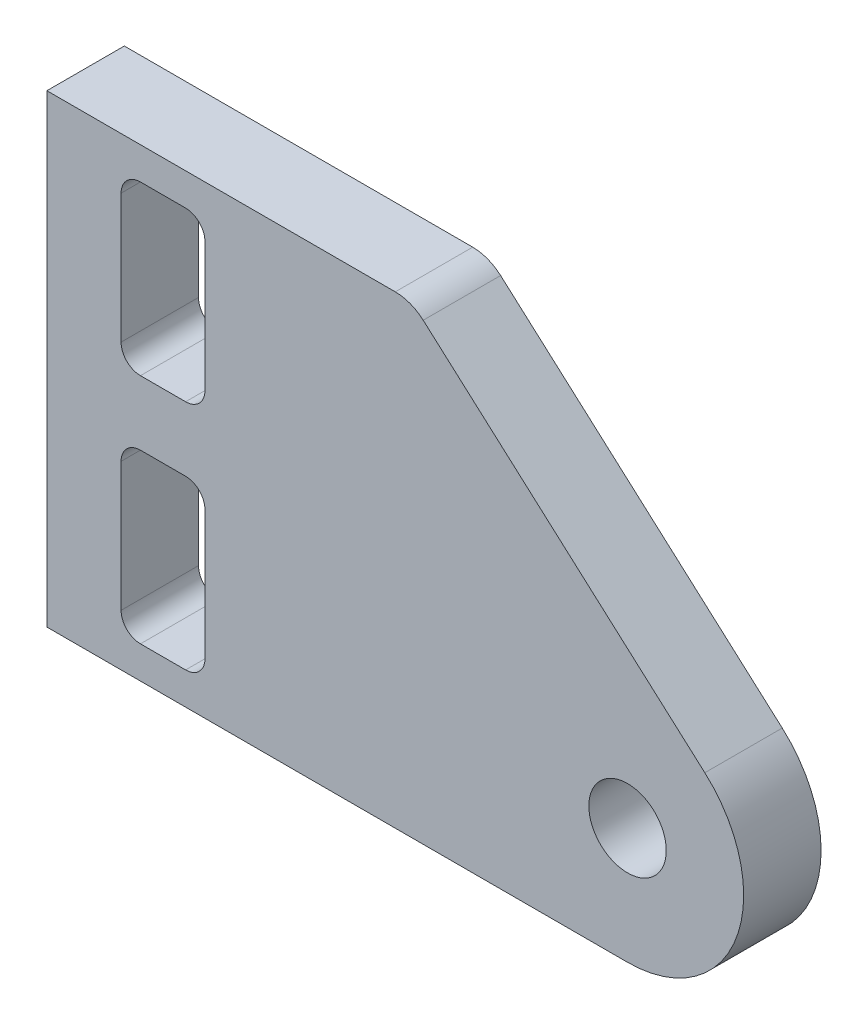
SolidWorks part; units mm, degrees
ref_plane "Alzado" through (0, 0, 0) normal (0, 0, 1) x (1, 0, 0)
ref_plane "Planta" through (0, 0, 0) normal (0, 1, 0) x (1, 0, 0)
ref_plane "Vista lateral" through (0, 0, 0) normal (1, 0, 0) x (0, 0, -1)
sketch "Model" plane through (0, 0, 0) normal (0, 0, 1) x (1, 0, 0)
  line L0 (201.0979, 264.6465) -> (178.5979, 264.6465)
  line L1 (182.2229, 265.8965) -> (183.9729, 265.8965)
  line L2 (184.7229, 266.6465) -> (184.7229, 271.6465)
  line L3 (183.9729, 272.3965) -> (182.2229, 272.3965)
  line L4 (181.4729, 271.6465) -> (181.4729, 266.6465)
  line L5 (192.0979, 282.6465) -> (178.5979, 282.6465)
  line L6 (193.1792, 282.2345) -> (204.0924, 272.5055)
  line L7 (182.2229, 274.896) -> (183.9729, 274.896)
  line L8 (184.7229, 275.646) -> (184.7229, 280.646)
  line L9 (183.9729, 281.396) -> (182.2229, 281.396)
  line L10 (181.4729, 280.646) -> (181.4729, 275.646)
  line L11 (178.5979, 282.6465) -> (178.5979, 264.6465)
  arc A0 (201.0979, 264.6465) -> (204.0924, 272.5055) centre (201.0979, 269.1465) ccw
  circle A1 centre (201.0979, 269.1465) radius 1.5
  arc A2 (181.4729, 266.6465) -> (182.2229, 265.8965) centre (182.2229, 266.6465) ccw
  arc A3 (183.9729, 265.8965) -> (184.7229, 266.6465) centre (183.9729, 266.6465) ccw
  arc A4 (184.7229, 271.6465) -> (183.9729, 272.3965) centre (183.9729, 271.6465) ccw
  arc A5 (182.2229, 272.3965) -> (181.4729, 271.6465) centre (182.2229, 271.6465) ccw
  arc A6 (193.1792, 282.2345) -> (192.0979, 282.6465) centre (192.0979, 281.0215) ccw
  arc A7 (181.4729, 275.646) -> (182.2229, 274.896) centre (182.2229, 275.646) ccw
  arc A8 (183.9729, 274.896) -> (184.7229, 275.646) centre (183.9729, 275.646) ccw
  arc A9 (184.7229, 280.646) -> (183.9729, 281.396) centre (183.9729, 280.646) ccw
  arc A10 (182.2229, 281.396) -> (181.4729, 280.646) centre (182.2229, 280.646) ccw
extrude "Saliente-Extruir1" add sketch "Model" along normal blind 3
